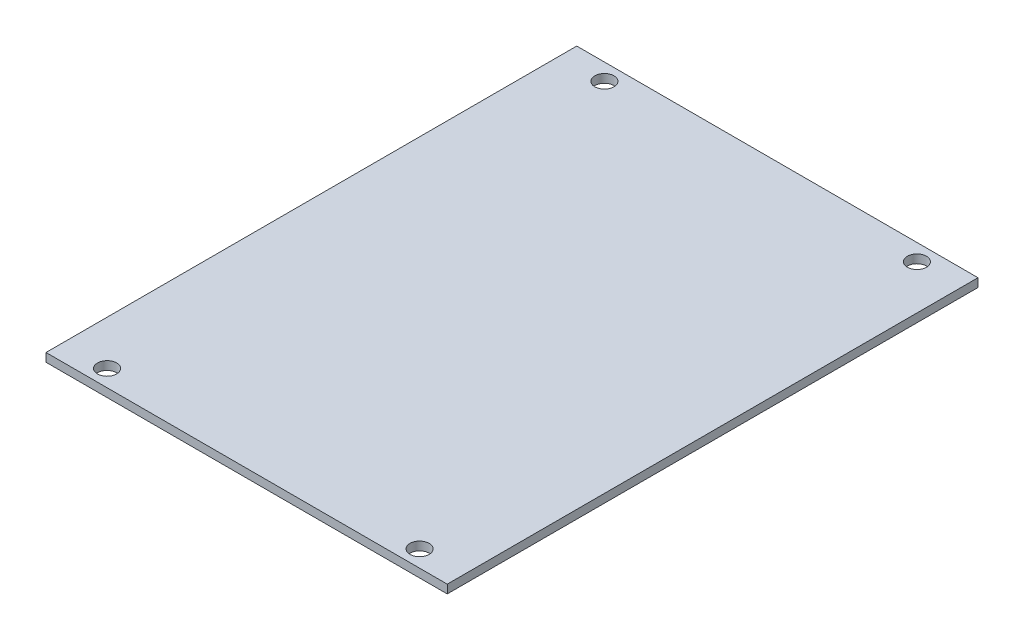
SolidWorks part; units mm, degrees
material "PET"
ref_plane "Front Plane" through (0, 0, 0) normal (0, 0, 1) x (1, 0, 0)
ref_plane "Top Plane" through (0, 0, 0) normal (0, 1, 0) x (1, 0, 0)
ref_plane "Right Plane" through (0, 0, 0) normal (1, 0, 0) x (0, 0, -1)
sketch "Sketch1" plane through (0, 0, 0) normal (0, 1, 0) x (1, 0, 0)
  line L1 (-35.9283, -47.5234) -> (35.9283, -47.5234)
  line L2 (-35.9283, -47.5234) -> (-35.9283, 47.5234)
  line L3 (-35.9283, 47.5234) -> (35.9283, 47.5234)
  line L4 (35.9283, -47.5234) -> (35.9283, 47.5234)
  line L5 (-35.9283, -47.5234) -> (35.9283, 47.5234) construction
  line L6 (-35.9283, 47.5234) -> (35.9283, -47.5234) construction
  point P0 (0, 0)
  dimension "D1" = 95.0468
  dimension "D2" = 71.8566
extrude "Boss-Extrude1" add sketch "Sketch1" along normal blind 1.524
sketch "Sketch2" plane through (0, 1.524, 0) normal (0, 1, 0) x (1, 0, 0)
  line L1 (27.9813, -44.5325) -> (-27.9813, -44.5325) construction
  line L2 (27.9813, -44.5325) -> (27.9813, 44.5326) construction
  line L3 (27.9813, 44.5326) -> (-27.9813, 44.5326) construction
  line L4 (-27.9813, -44.5325) -> (-27.9813, 44.5326) construction
  line L5 (27.9813, -44.5325) -> (-27.9813, 44.5326) construction
  line L6 (27.9813, 44.5326) -> (-27.9813, -44.5325) construction
  circle A0 centre (-27.9813, 44.5326) radius 1.7145
  circle A1 centre (27.9813, 44.5326) radius 1.7145
  circle A2 centre (27.9813, -44.5325) radius 1.7145
  circle A3 centre (-27.9813, -44.5325) radius 1.7145
  point P0 (0, 0)
  dimension "D1" = 3.429
  dimension "D2" = 89.0651
  dimension "D3" = 55.9625
extrude "Cut-Extrude1" cut sketch "Sketch2" against normal through all
